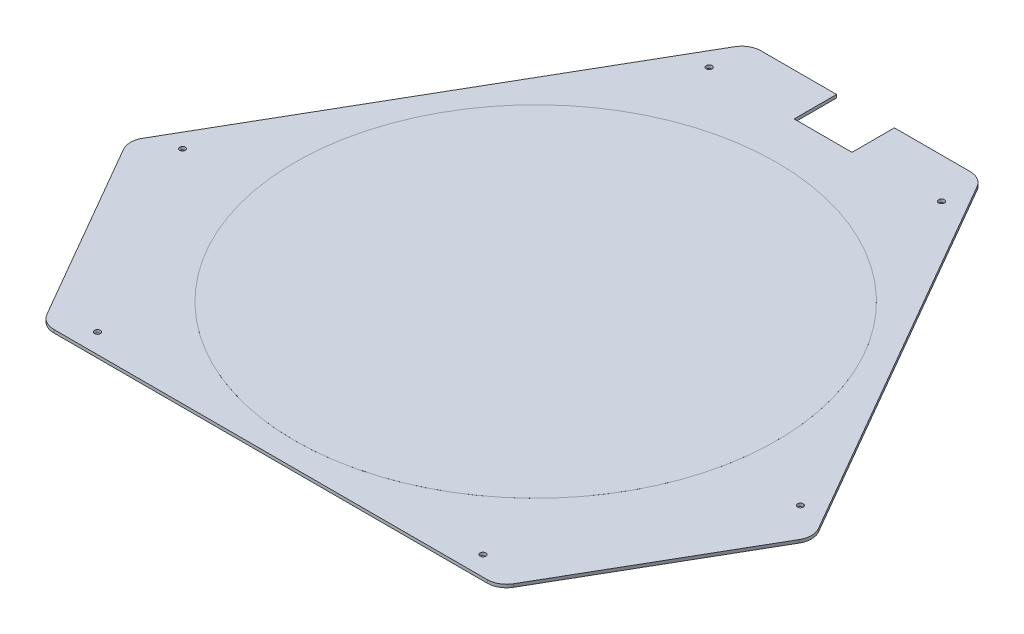
SolidWorks part; units mm, degrees
ref_plane "Спереди" through (0, 0, 0) normal (0, 0, 1) x (1, 0, 0)
ref_plane "Сверху" through (0, 0, 0) normal (0, 1, 0) x (1, 0, 0)
ref_plane "Справа" through (0, 0, 0) normal (1, 0, 0) x (0, 0, -1)
sketch "Эскиз1" plane through (0, 0, 0) normal (0, 1, 0) x (1, 0, 0)
  line L1 (178.157, -33.577) -> (60, 171.077)
  line L2 (60, 171.077) -> (-60, 171.077)
  line L3 (-60, 171.077) -> (-178.157, -33.577)
  line L4 (-178.157, -33.577) -> (-118.157, -137.5)
  line L5 (-118.157, -137.5) -> (118.157, -137.5)
  line L6 (118.157, -137.5) -> (178.157, -33.577)
  circle A0 centre (0, 0) radius 137.5 construction
  dimension "D1" = 120
  dimension "D3" = 275
extrude "База" add sketch "Эскиз1" along normal blind 1.6
fillet "Скругление1" radius 10 6 edges at (60, 0.8, -171.077) (-60, 0.8, -171.077) (-178.157, 0.8, 33.577) (-118.157, 0.8, 137.5) (178.157, 0.8, 33.577) (118.157, 0.8, 137.5)
sketch "Эскиз2" plane through (0, 1.6, 0) normal (0, 1, 0) x (1, 0, 0)
  line L0 (54.2265, 171.077) -> (-54.2265, 171.077) construction
  line L1 (-15, 171.077) -> (15, 171.077)
  line L2 (-15, 171.077) -> (-15, 149.077)
  line L3 (-15, 149.077) -> (15, 149.077)
  line L4 (15, 171.077) -> (15, 149.077)
  point P6 (0, 149.077)
  point P7 (0, 171.077)
  point P8 (0, 171.077)
  dimension "D1" = 22
  dimension "D2" = 30
extrude "Вырез-Вытянуть1" cut sketch "Эскиз2" against normal through all
sketch "Эскиз3" plane through (0, 1.6, 0) normal (0, 1, 0) x (1, 0, 0)
  circle A0 centre (0, 0) radius 125
  dimension "D1" = 250
extrude "АктивнаяЗона" add sketch "Эскиз3" along normal blind 0.01
hole_wizard "Отверстие 3мм" positions "Эскиз4" profile "Эскиз5" hole size "Ø3.0" standard "DIN" end condition through all
sketch "Эскиз4" plane through (0, 1.6, 0) normal (0, 1, 0) x (1, 0, 0)
  line L0 (-60.25, 150.2554) -> (60.25, 150.2554) construction
  line L1 (60.25, 150.2554) -> (160.25, -22.9497) construction
  line L2 (160.25, -22.9497) -> (100, -127.3057) construction
  line L3 (100, -127.3057) -> (-100, -127.3057) construction
  line L4 (-100, -127.3057) -> (-160.25, -22.9497) construction
  line L5 (-160.25, -22.9497) -> (-60.25, 150.2554) construction
  line L9 (-15, 149.077) -> (15, 149.077) construction
  line L10 (-112.3835, -137.5) -> (112.3835, -137.5) construction
  line L22 (0, 0) -> (0, 150.2554) construction
  line L25 (0, 0) -> (110.25, 63.6529) construction
  line L28 (0, 0) -> (130.125, -75.1277) construction
  line L31 (0, 0) -> (0, -127.3057) construction
  line L34 (0, 0) -> (-130.125, -75.1277) construction
  line L37 (0, 0) -> (-110.25, 63.6529) construction
  point P0 (-60.25, 150.2554)
  point P2 (60.25, 150.2554)
  point P4 (160.25, -22.9497)
  point P6 (100, -127.3057)
  point P8 (-100, -127.3057)
  point P10 (-160.25, -22.9497)
  point P31 (0, 149.077)
  point P32 (0, 150.2554)
  point P35 (0, -137.5)
  point P36 (0, -127.3057)
  dimension "D1" = 120.5
  dimension "D2" = 200
sketch "Эскиз5" plane through (-60.25, 1.6, -150.2554) normal (1, 0, 0) x (0, 0, 1)
  line L0 (0, 0) -> (0, 1.6)
  line L1 (0, 1.6) -> (1.5, 1.6)
  line L2 (1.5, 1.6) -> (1.5, 0)
  line L5 (1.5, 0) -> (0, 0)
  line L11 (0, -6.35) -> (0, 107.95) construction
  dimension "Диаметр сквозного отверстия" = 3
  dimension "Глубина сквозного отверстия" = 1.6
